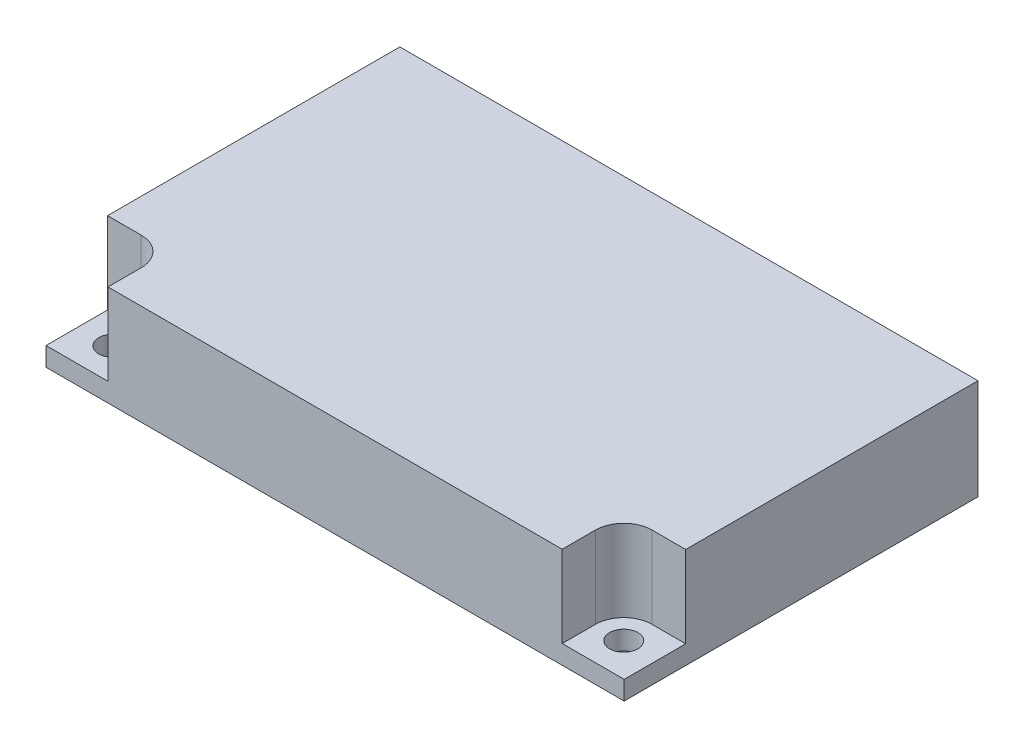
SolidWorks part; units mm, degrees
ref_plane "Front Plane" through (0, 0, 0) normal (0, 0, 1) x (1, 0, 0)
ref_plane "Top Plane" through (0, 0, 0) normal (0, 1, 0) x (1, 0, 0)
ref_plane "Right Plane" through (0, 0, 0) normal (1, 0, 0) x (0, 0, -1)
sketch "Sketch1" plane through (0, 0, 0) normal (0, 1, 0) x (1, 0, 0)
  line L1 (-23, -14.075) -> (23, -14.075)
  line L2 (-23, -14.075) -> (-23, 14.075)
  line L3 (-23, 14.075) -> (23, 14.075)
  line L4 (23, -14.075) -> (23, 14.075)
  line L5 (-23, -14.075) -> (23, 14.075) construction
  line L6 (-23, 14.075) -> (23, -14.075) construction
  line L7 (0, 0) -> (0, 14.075) construction
  circle A0 centre (20.32, -11.43) radius 1.125
  circle A2 centre (-20.32, -11.43) radius 1.125
  point P0 (0, 0)
  dimension "D3" = 2.25
  dimension "D1" = 46
  dimension "D2" = 28.15
  dimension "D4" = 11.43
  dimension "D5" = 20.32
extrude "Boss-Extrude1" add sketch "Sketch1" along normal blind 1.5
sketch "Sketch2" plane through (0, 1.5, 0) normal (0, 1, 0) x (1, 0, 0)
  line L0 (-18.07, -11.43) -> (-18.07, -14.075)
  line L1 (-23, -14.075) -> (23, -14.075) construction
  line L2 (-18.07, -14.075) -> (18.07, -14.075)
  line L3 (18.07, -14.075) -> (18.07, -11.43)
  line L4 (20.32, -9.18) -> (23, -9.18)
  line L5 (23, -14.075) -> (23, 14.075) construction
  line L6 (23, -9.18) -> (23, 14.075)
  line L7 (23, 14.075) -> (-23, 14.075)
  line L8 (-23, 14.075) -> (-23, -9.18)
  line L9 (-23, 14.075) -> (-23, -14.075) construction
  line L10 (-23, -9.18) -> (-20.32, -9.18)
  arc A0 (-18.07, -11.43) -> (-20.32, -9.18) centre (-20.32, -11.43) ccw
  arc A1 (20.32, -9.18) -> (18.07, -11.43) centre (20.32, -11.43) ccw
  dimension "D1" = 4.5
extrude "Boss-Extrude2" add sketch "Sketch2" along normal offset from surface (6.5 mm away) 8 up to face at (20.32, 0, 12.555)
